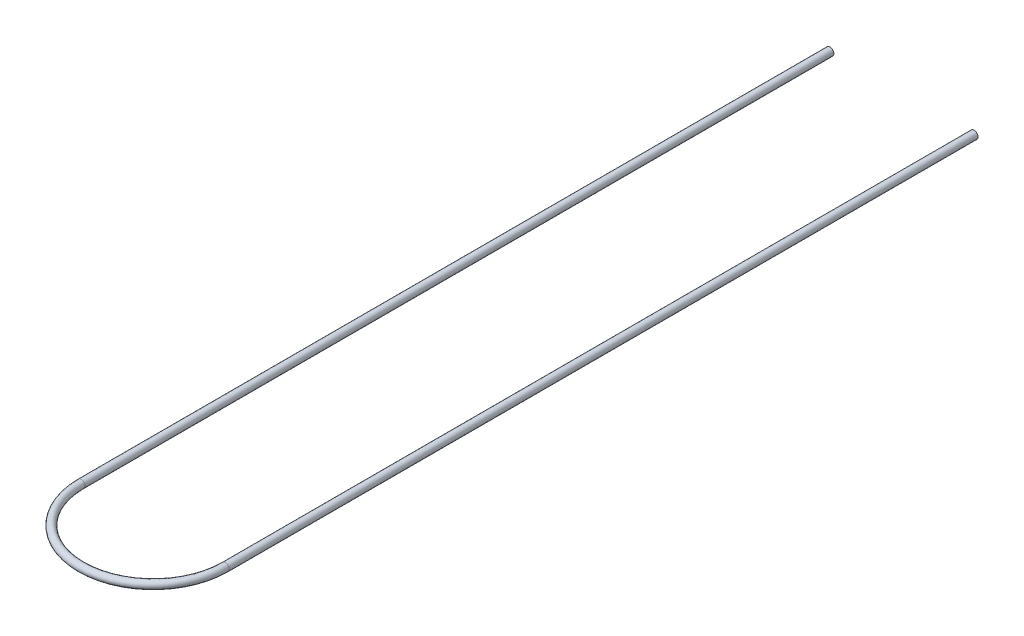
SolidWorks part; units mm, degrees
ref_plane "Front Plane" through (0, 0, 0) normal (0, 0, 1) x (1, 0, 0)
ref_plane "Top Plane" through (0, 0, 0) normal (0, 1, 0) x (1, 0, 0)
ref_plane "Right Plane" through (0, 0, 0) normal (1, 0, 0) x (0, 0, -1)
sketch "Sketch1" plane through (0, 0, 0) normal (0, 1, 0) x (1, 0, 0)
  line L0 (372, -300) -> (372, -2440)
  line L2 (-40, -300) -> (-40, -2440)
  arc A0 (-40, -2440) -> (372, -2440) centre (166, -2440) ccw
  dimension "D1" = 2140
  dimension "D2" = 412
ref_plane "Plane1" through (372, 0, 300) normal (0, 0, -1) x (-1, 0, 0)
sketch "Sketch2" plane through (372, 0, 300) normal (0, 0, -1) x (-1, 0, 0)
  circle A0 centre (0, 0) radius 9.95
  circle A1 centre (0, 0) radius 11.1
  dimension "D1" = 22.2
  dimension "D2" = 19.9
sweep "Sweep1" add profiles "Sketch2" path "Sketch1"
